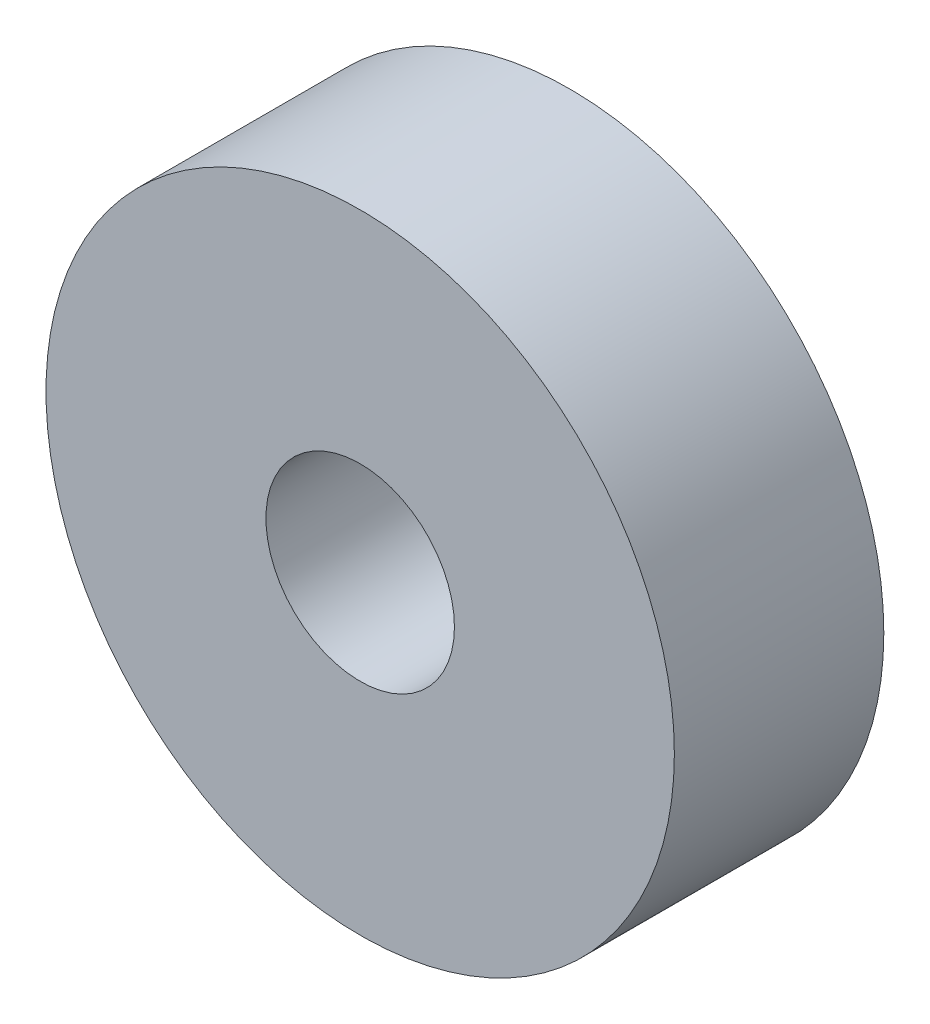
SolidWorks part; units mm, degrees
ref_plane "前视基准面" through (0, 0, 0) normal (0, 0, 1) x (1, 0, 0)
ref_plane "上视基准面" through (0, 0, 0) normal (0, 1, 0) x (1, 0, 0)
ref_plane "右视基准面" through (0, 0, 0) normal (1, 0, 0) x (0, 0, -1)
sketch "草图1" plane through (0, 0, 0) normal (0, 0, 1) x (1, 0, 0)
  circle A0 centre (0, 0) radius 4.5
  circle A1 centre (0, 0) radius 15
  dimension "D1" = 9
  dimension "D2" = 30
extrude "凸台-拉伸1" add sketch "草图1" along normal blind 10
